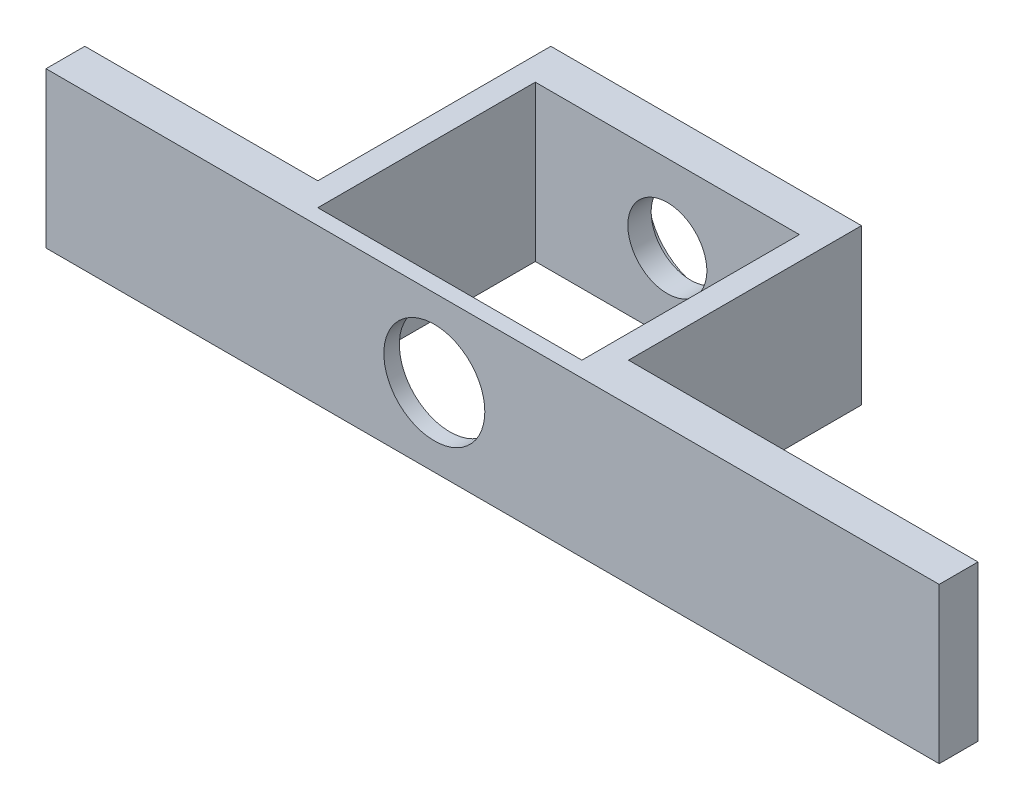
SolidWorks part; units mm, degrees
ref_plane "Front Plane" through (0, 0, 0) normal (0, 0, 1) x (1, 0, 0)
ref_plane "Top Plane" through (0, 0, 0) normal (0, 1, 0) x (1, 0, 0)
ref_plane "Right Plane" through (0, 0, 0) normal (1, 0, 0) x (0, 0, -1)
sketch "Sketch1" plane through (0, 0, 0) normal (0, 0, 1) x (1, 0, 0)
  line L1 (-20, -10) -> (20, -10)
  line L2 (-20, -10) -> (-20, 10)
  line L3 (-20, 10) -> (20, 10)
  line L4 (20, -10) -> (20, 10)
  line L5 (-20, -10) -> (20, 10) construction
  line L6 (-20, 10) -> (20, -10) construction
  point P0 (0, 0)
  dimension "D1" = 40
  dimension "D2" = 20
extrude "Boss-Extrude1" add sketch "Sketch1" along normal blind 5
sketch "Sketch2" plane through (0, 0, 5) normal (0, 0, 1) x (1, 0, 0)
  line L0 (-20, -10) -> (20, -10) construction
  line L1 (-20, 10) -> (-17, 10)
  line L2 (-20, 10) -> (-20, -10)
  line L3 (-20, -10) -> (-17, -10)
  line L4 (-17, 10) -> (-17, -10)
  line L6 (20, 10) -> (17, 10)
  line L7 (20, 10) -> (20, -10)
  line L8 (20, -10) -> (17, -10)
  line L9 (17, 10) -> (17, -10)
  dimension "D1" = 3
  dimension "D2" = 3
extrude "Boss-Extrude2" add sketch "Sketch2" along normal blind 30
sketch "Sketch3" plane through (20, 0, 0) normal (1, 0, 0) x (0, 0, -1)
  line L0 (-35, -10) -> (0, -10) construction
  line L1 (-35, 10) -> (-30, 10)
  line L2 (-35, 10) -> (-35, -10)
  line L3 (-35, -10) -> (-30, -10)
  line L4 (-30, 10) -> (-30, -10)
  dimension "D1" = 5
extrude "Boss-Extrude3" add sketch "Sketch3" along normal blind 45
sketch "Sketch4" plane through (-20, 0, 0) normal (-1, 0, 0) x (0, 0, 1)
  line L0 (35, -10) -> (0, -10) construction
  line L1 (35, 10) -> (30, 10)
  line L2 (35, 10) -> (35, -10)
  line L3 (35, -10) -> (30, -10)
  line L4 (30, 10) -> (30, -10)
  dimension "D1" = 5
extrude "Boss-Extrude4" add sketch "Sketch4" along normal blind 30
sketch "Sketch5" plane through (0, 0, 35) normal (0, 0, 1) x (1, 0, 0)
  line L0 (-17, -10) -> (-17, 10) construction
  line L1 (-17, 10) -> (17, 10)
  line L2 (-17, 10) -> (-17, -10)
  line L3 (-17, -10) -> (17, -10)
  line L4 (17, 10) -> (17, -10)
extrude "Boss-Extrude5" add sketch "Sketch5" against normal blind 2
sketch "Sketch6" plane through (0, 0, 0) normal (0, 0, -1) x (-1, 0, 0)
  line L0 (0, 10) -> (0, -10) construction
  line L1 (-20, 10) -> (20, 10) construction
  line L2 (20, -10) -> (-20, -10) construction
  circle A0 centre (0, 0) radius 7.5
  dimension "D1" = 15
extrude "Cut-Extrude1" cut sketch "Sketch6" against normal blind 2
sketch "Sketch7" plane through (0, 0, 2) normal (0, 0, -1) x (-1, 0, 0)
  circle A0 centre (0, 0) radius 5.0855
extrude "Cut-Extrude2" cut sketch "Sketch7" against normal blind 5
sketch "Sketch8" plane through (0, 0, 35) normal (0, 0, 1) x (1, 0, 0)
  line L0 (7.5, 10) -> (7.5, -10) construction
  line L1 (65, 10) -> (-50, 10) construction
  line L2 (-50, -10) -> (65, -10) construction
  circle A0 centre (0, 0) radius 6.5
  dimension "D1" = 13
extrude "Cut-Extrude3" cut sketch "Sketch8" against normal blind 13 contours A0
